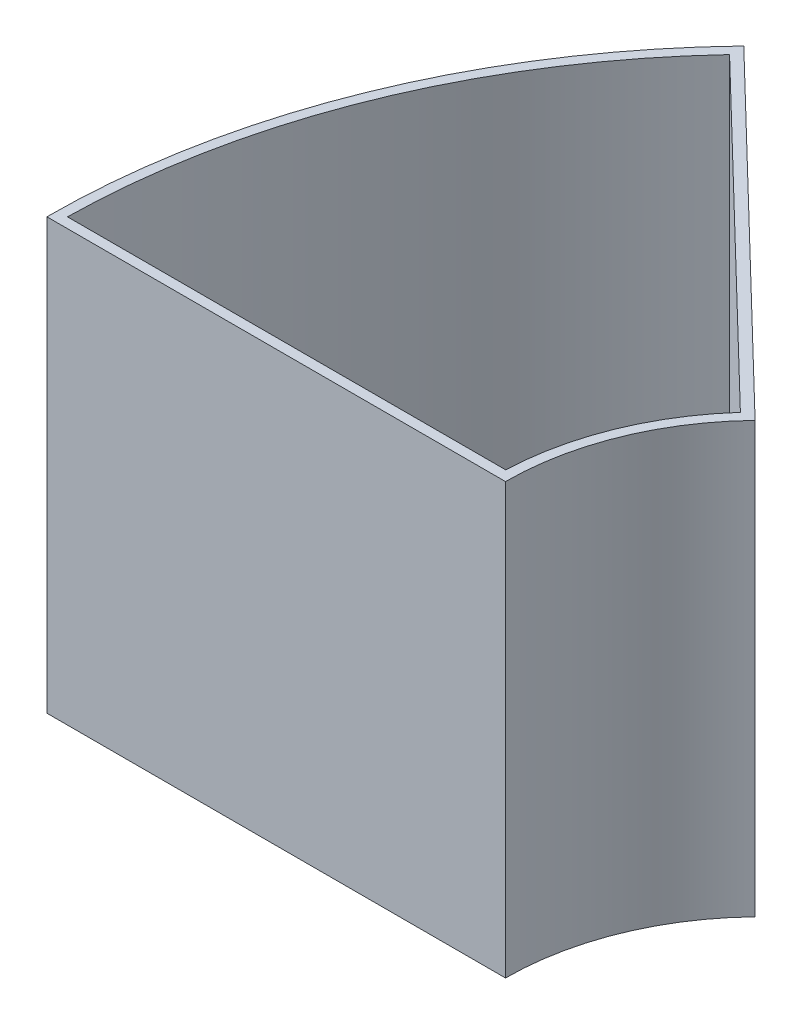
SolidWorks part; units mm, degrees
ref_plane "Alzado" through (0, 0, 0) normal (0, 0, 1) x (1, 0, 0)
ref_plane "Planta" through (0, 0, 0) normal (0, 1, 0) x (1, 0, 0)
ref_plane "Vista lateral" through (0, 0, 0) normal (1, 0, 0) x (0, 0, -1)
sketch "Croquis1" plane through (0, 0, 0) normal (0, 1, 0) x (1, 0, 0)
  line L0 (0, 0) -> (-75, 0) construction
  line L1 (0, 0) -> (-50.2099, 48.4872) construction
  line L2 (-25, 0) -> (-69.8, 0)
  line L4 (-50.2099, 48.4872) -> (-17.9835, 17.3665)
  circle A0 centre (0, 0) radius 75 construction
  circle A1 centre (0, 0) radius 69.8 construction
  circle A2 centre (0, 0) radius 25 construction
  arc A3 (-25, 0) -> (-17.9835, 17.3665) centre (0, 0) cw
  arc A4 (-69.8, 0) -> (-50.2099, 48.4872) centre (0, 0) cw
  dimension "D1" = 150
  dimension "D2" = 5.2
  dimension "D3" = 50
  dimension "D4" = 44
extrude "Saliente-Extruir1" add sketch "Croquis1" along normal blind 40
shell "Vaciado1" thickness 1
sketch "Croquis4" plane through (0, 0, 0) normal (0, -1, 0) x (1, 0, 0)
  line L0 (-25, 0) -> (-69.8, 0)
  line L1 (-17.9835, -17.3665) -> (-50.2099, -48.4872)
  arc A0 (-69.8, 0) -> (-50.2099, -48.4872) centre (0, 0) ccw
  arc A1 (-25, 0) -> (-17.9835, -17.3665) centre (0, 0) ccw
extrude "Saliente-Extruir3" add sketch "Croquis4" along normal blind 2
sketch "Croquis2" plane through (0, -2, 0) normal (0, 1, 0) x (1, 0, 0)
  line L0 (-38.9097, 27.2449) -> (-30.7182, 21.5091)
  line L1 (-46.9152, 7.4306) -> (-37.0383, 5.8663)
  line L2 (-17.9835, 17.3665) -> (-50.2099, 48.4872) construction
  circle A0 centre (0, 0) radius 37.5 construction
  circle A1 centre (0, 0) radius 47.5 construction
  arc A2 (-37.0383, 5.8663) -> (-30.7182, 21.5091) centre (0, 0) cw
  arc A3 (-46.9152, 7.4306) -> (-38.9097, 27.2449) centre (0, 0) cw
  dimension "D1" = 75
  dimension "D2" = 95
  dimension "D3" = 9
  dimension "D4" = 26
extrude "Cortar-Extruir1" cut sketch "Croquis2" along normal blind 2
sketch "Croquis5" plane through (0, 1, 0) normal (0, 1, 0) x (1, 0, 0)
  line L0 (0, 0) -> (-64.7174, 26.1475) construction
  arc A1 (-50.2099, 48.4872) -> (-69.8, 0) centre (0, 0) ccw construction
  circle A2 centre (-55.631, 22.4764) radius 2.5
  dimension "D1" = 5
  dimension "D2" = 60
extrude "Cortar-Extruir2" cut sketch "Croquis5" against normal blind 2
